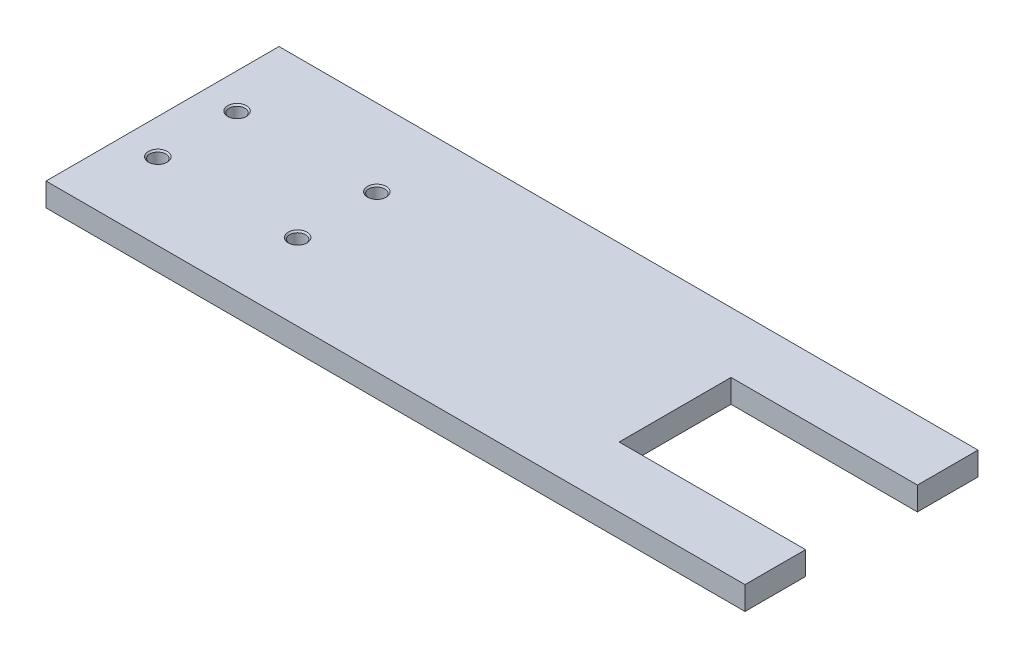
SolidWorks part; units mm, degrees
material "AISI 1045 Aço, trefilado"
ref_plane "Plano frontal" through (0, 0, 0) normal (0, 0, 1) x (1, 0, 0)
ref_plane "Plano superior" through (0, 0, 0) normal (0, 1, 0) x (1, 0, 0)
ref_plane "Plano direito" through (0, 0, 0) normal (1, 0, 0) x (0, 0, -1)
sketch "Esboço1" plane through (0, 0, 0) normal (0, 1, 0) x (1, 0, 0)
  line L0 (70, 24) -> (150, 24)
  line L1 (150, -50) -> (-150, -50)
  line L2 (150, -50) -> (150, -24)
  line L3 (150, 50) -> (-150, 50)
  line L4 (-150, -50) -> (-150, 50)
  line L5 (150, -50) -> (-150, 50) construction
  line L6 (150, 50) -> (-150, -50) construction
  line L7 (70, 24) -> (70, -24)
  line L8 (70, -24) -> (150, -24)
  line L9 (150, 24) -> (150, 50)
  point P0 (0, 0)
  dimension "D1" = 300
  dimension "D2" = 100
  dimension "D3" = 48
  dimension "D4" = 26
  dimension "D5" = 80
extrude "Ressalto-extrusão1" add sketch "Esboço1" along normal mid plane 10
hole_wizard "Furo roscado de M82" positions "3DSketch1" profile "Esboço4" tap size "M8" standard "ISO" end condition through all
sketch3d "3DSketch1"
  line L0 (-150, 5, 50) -> (150, 5, 50) construction
  line L1 (150, 5, -50) -> (-150, 5, -50) construction
  line L2 (150, 5, -24) -> (150, 5, -50) construction
  line L3 (150, 5, 50) -> (150, 5, 24) construction
  point P0 (-135, 5, -17)
  point P2 (-135, 5, 17)
  point P4 (-75, 5, 17)
  point P6 (-75, 5, -17)
  dimension "D1" = 34
  dimension "D2" = 33
  dimension "D3" = 33
  dimension "D4" = 33
  dimension "D5" = 225
  dimension "D6" = 225
  dimension "D7" = 60
  dimension "D8" = 60
sketch "Esboço4" plane through (-135, 5, -17) normal (1, 0, 0) x (0, 0, 1)
  line L0 (0, 0) -> (0, 10)
  line L1 (0, 10) -> (3.4, 10)
  line L2 (3.4, 10) -> (3.4, 0.625)
  line L3 (3.4, 0.625) -> (4.025, 0)
  line L5 (4.025, 0) -> (0, 0)
  line L6 (-3.4, 0.625) -> (-4.025, 0) construction
  line L11 (0, -6.35) -> (0, 107.95) construction
  dimension "Thru Tap Drill Dia." = 6.8
  dimension "Thru Tap Drill Depth" = 10
  dimension "Near C'Sink Dia." = 8.05
  dimension "Near C'Sink Angle" = 90
cosmetic thread "Rosca de furo5"
cosmetic thread "Rosca de furo6"
cosmetic thread "Rosca de furo7"
cosmetic thread "Rosca de furo8"
